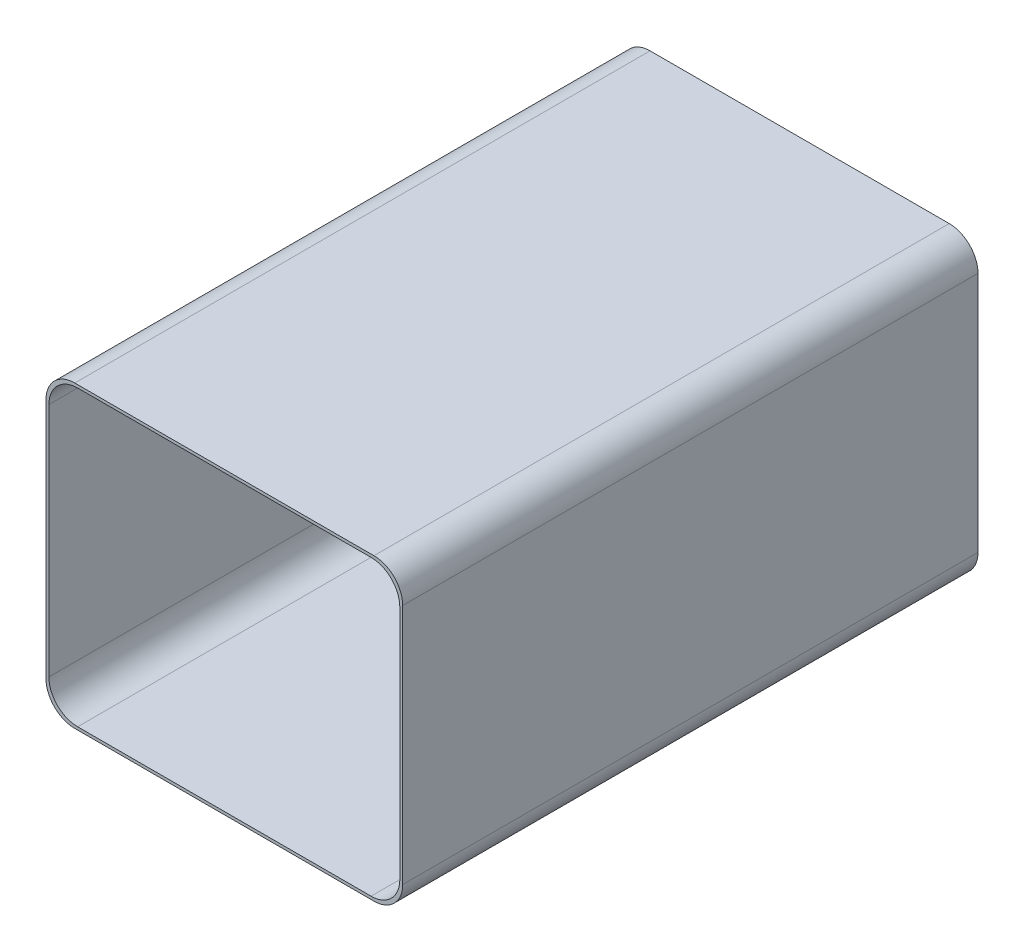
SolidWorks part; units mm, degrees
ref_plane "前视基准面" through (0, 0, 0) normal (0, 0, 1) x (1, 0, 0)
ref_plane "上视基准面" through (0, 0, 0) normal (0, 1, 0) x (1, 0, 0)
ref_plane "右视基准面" through (0, 0, 0) normal (1, 0, 0) x (0, 0, -1)
other "Configuration Table"
sketch "草图1" plane through (0, 0, 0) normal (0, 0, 1) x (1, 0, 0)
  line L1 (20.8379, 75.2345) -> (540.8379, 75.2345)
  line L2 (-29.1621, 25.2345) -> (-29.1621, -394.7655)
  line L3 (20.8379, -444.7655) -> (540.8379, -444.7655)
  line L4 (590.8379, 25.2345) -> (590.8379, -394.7655)
  line L5 (25.8379, 70.2345) -> (535.8379, 70.2345)
  line L6 (-24.1621, 20.2345) -> (-24.1621, -389.7655)
  line L7 (25.8379, -439.7655) -> (535.8379, -439.7655)
  line L8 (585.8379, 20.2345) -> (585.8379, -389.7655)
  arc A0 (540.8379, -444.7655) -> (590.8379, -394.7655) centre (540.8379, -394.7655) ccw
  arc A1 (535.8379, -439.7655) -> (585.8379, -389.7655) centre (535.8379, -389.7655) ccw
  arc A2 (-29.1621, -394.7655) -> (20.8379, -444.7655) centre (20.8379, -394.7655) ccw
  arc A3 (-24.1621, -389.7655) -> (25.8379, -439.7655) centre (25.8379, -389.7655) ccw
  arc A4 (540.8379, 75.2345) -> (590.8379, 25.2345) centre (540.8379, 25.2345) cw
  arc A5 (535.8379, 70.2345) -> (585.8379, 20.2345) centre (535.8379, 20.2345) cw
  arc A6 (25.8379, 70.2345) -> (-24.1621, 20.2345) centre (25.8379, 20.2345) ccw
  arc A7 (20.8379, 75.2345) -> (-29.1621, 25.2345) centre (20.8379, 25.2345) ccw
  point P14 (-29.1621, -444.7655)
  point P17 (-24.1621, -439.7655)
  point P20 (590.8379, 75.2345)
  point P23 (585.8379, 70.2345)
  point P26 (-24.1621, 70.2345)
  point P29 (-29.1621, 75.2345)
  dimension "D7" = 50
  dimension "D1" = 620
  dimension "D2" = 520
  dimension "D3" = 610
  dimension "D4" = 510
  dimension "D5" = 5
  dimension "D6" = 5
extrude "凸台-拉伸2" add sketch "草图1" along normal blind 1000
